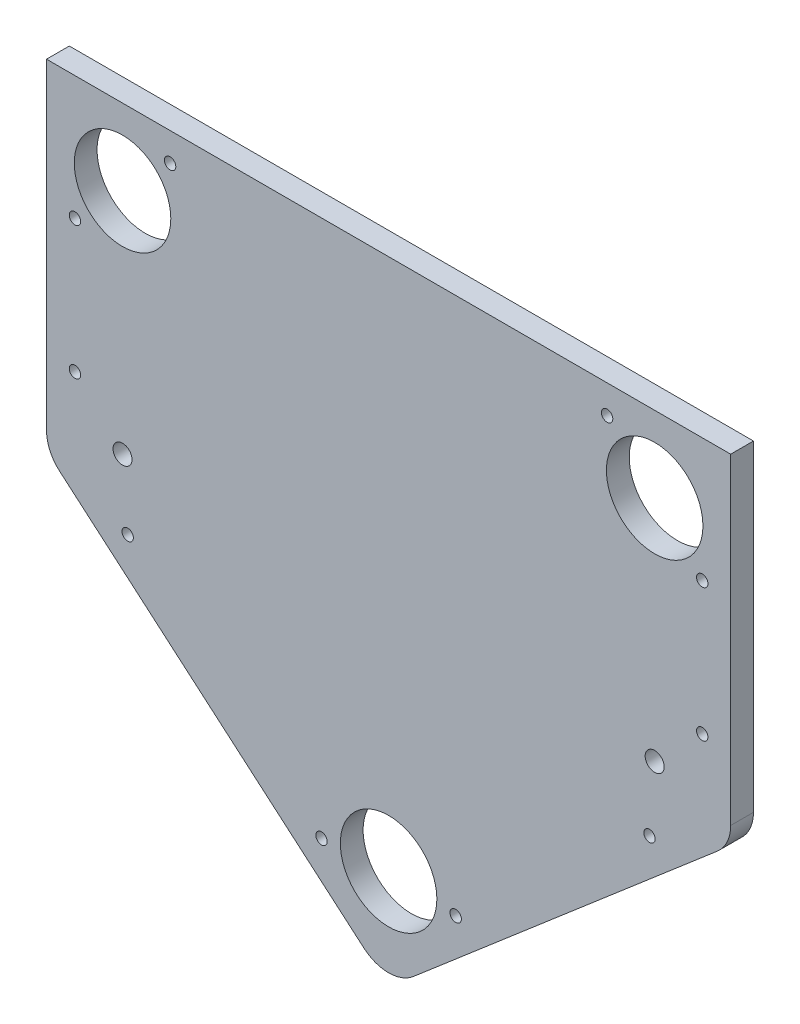
SolidWorks part; units mm, degrees
ref_plane "Front Plane" through (0, 0, 0) normal (0, 0, 1) x (1, 0, 0)
ref_plane "Top Plane" through (0, 0, 0) normal (0, 1, 0) x (1, 0, 0)
ref_plane "Right Plane" through (0, 0, 0) normal (1, 0, 0) x (0, 0, -1)
sketch "Sketch1" plane through (0, 0, 0) normal (0, 0, 1) x (1, 0, 0)
  line L0 (-70, 60) -> (70, 60) construction
  line L1 (-70, 0) -> (70, 0) construction
  line L2 (-82.5158, 47.4842) -> (-70, 60) construction
  line L3 (0, -60) -> (-70, 0) construction
  line L4 (0, -60) -> (-17.6479, -61.3575) construction
  line L5 (-68.6425, -17.6479) -> (-70, 0) construction
  line L6 (0, -60) -> (0, 60) construction
  line L7 (-90, 80) -> (90, 80)
  line L8 (90, 80) -> (90, -9.1987)
  line L9 (90, -9.1987) -> (0, -86.3416)
  line L10 (0, -86.3416) -> (-90, -9.1987)
  line L11 (-90, -9.1987) -> (-90, 80)
  circle A0 centre (-70, 60) radius 12.7
  circle A1 centre (70, 60) radius 12.7
  circle A2 centre (-70, 0) radius 2.5
  circle A3 centre (70, 0) radius 2.5
  circle A4 centre (0, -60) radius 12.7
  circle A5 centre (-82.5158, 47.4842) radius 1.5
  circle A6 centre (-57.4842, 72.5158) radius 1.5
  circle A7 centre (-82.5158, 12.5158) radius 1.5
  circle A8 centre (-68.6425, -17.6479) radius 1.5
  circle A9 centre (-17.6479, -61.3575) radius 1.5
  circle A10 centre (-70, 0) radius 12.7 construction
  circle A11 centre (70, 0) radius 12.7 construction
  circle A12 centre (-70, 0) radius 17.7 construction
  circle A13 centre (-70, 60) radius 17.7 construction
  circle A14 centre (0, -60) radius 17.7 construction
  circle A15 centre (17.6479, -61.3575) radius 1.5
  circle A16 centre (68.6425, -17.6479) radius 1.5
  circle A17 centre (82.5158, 12.5158) radius 1.5
  circle A18 centre (82.5158, 47.4842) radius 1.5
  circle A19 centre (57.4842, 72.5158) radius 1.5
  point P12 (0, 60)
  point P45 (0, 80)
  dimension "D1" = 25.4
  dimension "D2" = 5
  dimension "D5" = 3
  dimension "D3" = 60
  dimension "D4" = 60
  dimension "D6" = 5
  dimension "D7" = 135
  dimension "D8" = 45
  dimension "D9" = 140
  dimension "D10" = 45
  dimension "D11" = 20
  dimension "D12" = 20
  dimension "D13" = 20
  dimension "D14" = 20
  dimension "D15" = 20
extrude "Boss-Extrude1" add sketch "Sketch1" along normal blind 6
fillet "Fillet1" radius 10 3 edges at (-90, -9.1987, 3) (90, -9.1987, 3) (0, -86.3416, 3)
sketch "Sketch4" plane through (0, 0, 0) normal (0, 0, -1) x (-1, 0, 0)
  line L0 (-19.1479, -61.3575) -> (-22, -61.3575)
  line L1 (-5.5851, -80) -> (22, -80)
  line L3 (-22, -40) -> (22, -40)
  line L4 (22, -80) -> (22, -40)
  line L5 (-14.032, -72.7564) -> (22, -40) construction
  line L6 (-22, -40) -> (22, -80) construction
  line L8 (-16.1419, -61.364) -> (-15.7645, -71.2706)
  line L9 (-16.1497, -61.2827) -> (-16.1419, -61.364)
  line L10 (-5.5851, -80) -> (-15.7645, -71.2706)
  line L11 (-22, -61.3575) -> (-22, -40)
  circle A0 centre (0, -60) radius 12.7
  arc A1 (-19.1479, -61.3575) -> (-16.1497, -61.2827) centre (-17.6479, -61.3575) cw
  circle A2 centre (-17.6479, -61.3575) radius 1.5 construction
  arc A3 (-19.1479, -61.3575) -> (-16.1497, -61.2827) centre (-17.6479, -61.3575) cw
equation "\"carbon_fiber_tube_diam\"= 1in"
equation "\"clip_tube_diam\"= 6mm"
equation "\"D1@Sketch1\"=\"carbon_fiber_tube_diam\""
